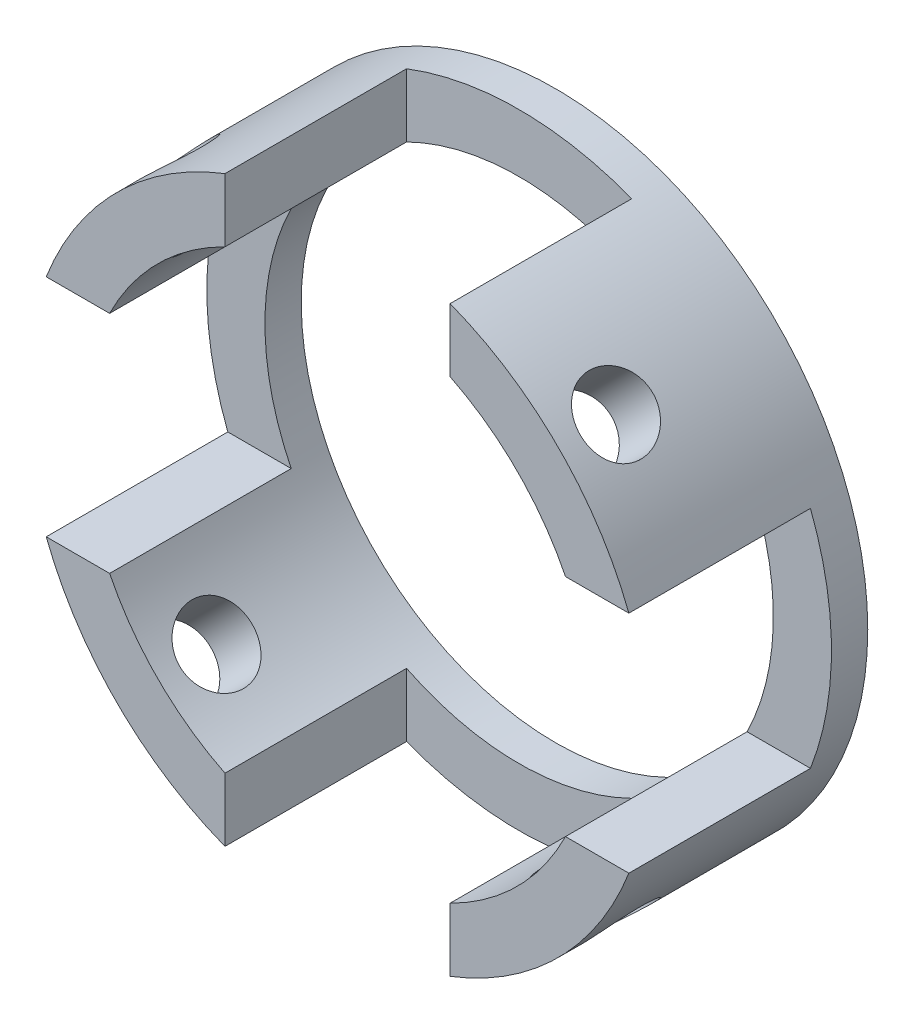
SolidWorks part; units mm, degrees
material "201 Annealed Stainless Steel (SS)"
ref_plane "前视基准面" through (0, 0, 0) normal (0, 0, 1) x (1, 0, 0)
ref_plane "上视基准面" through (0, 0, 0) normal (0, 1, 0) x (1, 0, 0)
ref_plane "右视基准面" through (0, 0, 0) normal (1, 0, 0) x (0, 0, -1)
other "Configuration Table"
sketch "Sketch1" plane through (0, 0, 0) normal (0, 0, 1) x (1, 0, 0)
  circle A0 centre (0, 0) radius 3.5
  circle A1 centre (0, 0) radius 4.3
  dimension "D1" = 7
  dimension "D2" = 8.6
extrude "Boss-Extrude1" add sketch "Sketch1" along normal blind 0.5
sketch "Sketch2" plane through (0, 0, 0.5) normal (0, 0, 1) x (1, 0, 0)
  line L0 (4.0109, 1.55) -> (3.1381, 1.55)
  line L1 (-4.0109, 1.55) -> (-3.1381, 1.55)
  line L5 (1.55, 4.0109) -> (1.55, 3.1381)
  line L6 (1.55, -4.0109) -> (1.55, -3.1381)
  line L8 (-1.55, 4.0109) -> (-1.55, 3.1381)
  line L11 (4.0109, -1.55) -> (3.1381, -1.55)
  line L12 (-4.0109, -1.55) -> (-3.1381, -1.55)
  line L13 (-1.55, -4.0109) -> (-1.55, -3.1381)
  arc A0 (-3.1381, 1.55) -> (-1.55, 3.1381) centre (0, 0) cw
  arc A1 (-1.55, 4.0109) -> (-4.0109, 1.55) centre (0, 0) ccw
  arc A2 (1.55, 3.1381) -> (3.1381, 1.55) centre (0, 0) cw
  arc A3 (4.0109, 1.55) -> (1.55, 4.0109) centre (0, 0) ccw
  arc A4 (3.1381, -1.55) -> (1.55, -3.1381) centre (0, 0) cw
  arc A5 (1.55, -4.0109) -> (4.0109, -1.55) centre (0, 0) ccw
  arc A6 (-1.55, -3.1381) -> (-3.1381, -1.55) centre (0, 0) cw
  arc A7 (-4.0109, -1.55) -> (-1.55, -4.0109) centre (0, 0) ccw
  point P0 (0, 0)
  point P6 (0, 0)
  point P25 (0, 0)
  dimension "D3" = 4.3
  dimension "D7" = 3.5
  dimension "D1" = 4
  dimension "D2" = 1.55
  dimension "D4" = 1.55
  dimension "D5" = 1.55
  dimension "D6" = 1.55
extrude "Boss-Extrude2" add sketch "Sketch2" along normal blind 2.5
sketch "Sketch3" plane through (0, 0, 0.5) normal (0, 0, 1) x (1, 0, 0)
  line L0 (0, 0) -> (3.0406, 3.0406) construction
  line L1 (0, 0) -> (3.0406, -3.0406) construction
  arc A0 (4.0109, 1.55) -> (1.55, 4.0109) centre (0, 0) ccw construction
  arc A1 (1.55, -4.0109) -> (4.0109, -1.55) centre (0, 0) ccw construction
ref_plane "Plane1" through (-3.0406, 3.0406, 0) normal (-0.7071, 0.7071, 0) x (0.7071, 0.7071, 0)
ref_plane "Plane2" through (3.0406, 3.0406, 0) normal (0.7071, 0.7071, 0) x (0, 0, -1)
sketch "Sketch5" plane through (3.0406, 3.0406, 0) normal (0.7071, 0.7071, 0) x (0, 0, -1)
  line L0 (0, -4.3) -> (0, 4.3) construction
  circle A0 centre (-2.2, 0) radius 0.5
  dimension "D1" = 1
  dimension "D2" = 2.2
extrude "Cut-Extrude2" cut sketch "Sketch5" against normal blind 3
pattern_circular "CirPattern1" count 4 over 360 about axis through (0, 0, 0.5) along (0, 0, -1) of "Cut-Extrude2"
